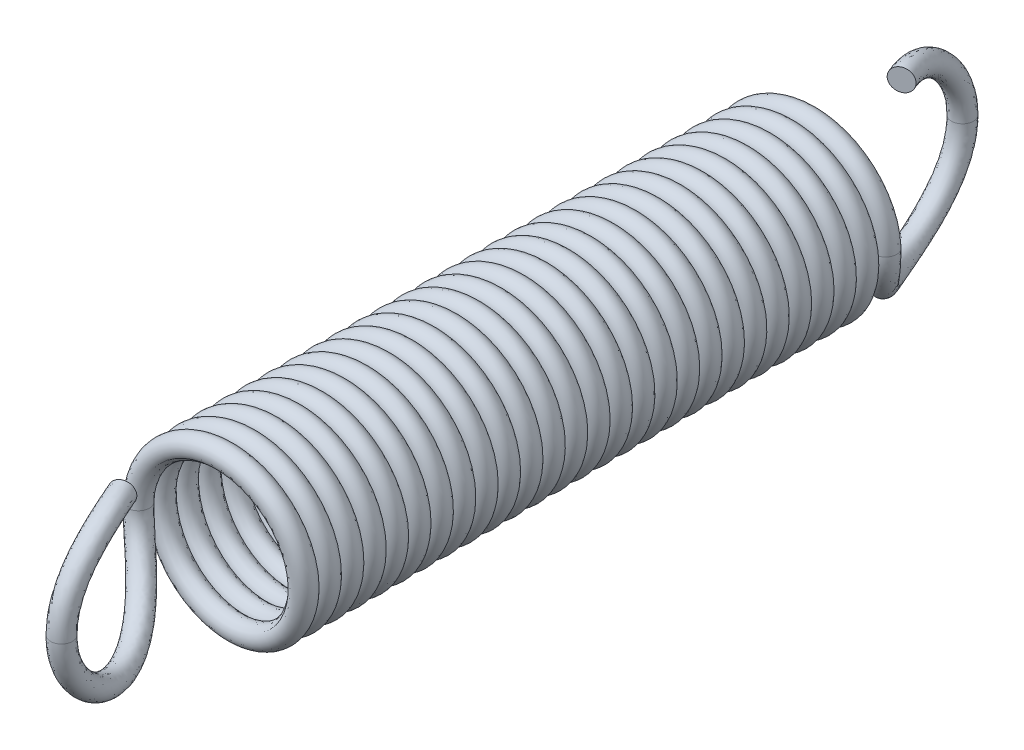
SolidWorks part; units mm, degrees
ref_plane "Front Plane" through (0, 0, 0) normal (0, 0, 1) x (1, 0, 0)
ref_plane "Top Plane" through (0, 0, 0) normal (0, 1, 0) x (1, 0, 0)
ref_plane "Right Plane" through (0, 0, 0) normal (1, 0, 0) x (0, 0, -1)
sketch "Sketch1" plane through (0, 0, 0) normal (1, 0, 0) x (0, 0, -1)
  line L0 (-5, 0) -> (5, 0) construction
  line L1 (5, 0) -> (14.53, 0) construction
  line L2 (-5, 1) -> (-5, -1) construction
  point P4 (0, 0)
  point P6 (-4.75, 0)
  point P9 (-5, 0)
  dimension "OD" = 2
  dimension "Wire Diameter" = 0.25
  dimension "Length" = 10
  dimension "Extended Length" = 19.53
sketch "Sketch2" plane through (0, 0, 0) normal (1, 0, 0) x (0, 0, -1)
  line L1 (-5, 0) -> (-5.25, 0) construction
  line L2 (-4.25, -0.75) -> (-4.25, -1) construction
  line L3 (0, 0) -> (0, 1) construction
  line L4 (-5, 0) -> (-4.75, 0) construction
  line L5 (-5, 0) -> (5, 0) construction
  line L6 (4.25, -0.75) -> (4.25, -1) construction
  line L7 (5, 0) -> (5.25, 0) construction
  line L8 (-4.25, -0.75) -> (4.25, -0.75) construction
  line L9 (-4.25, -1) -> (4.25, -1) construction
  line L10 (-3.25, 0) -> (-3.5, 0) construction
  line L11 (3.5, 0) -> (3.25, 0) construction
  line L12 (-5, 1) -> (-4.25, 1) construction
  circle A0 centre (-4.25, 0) radius 0.75 construction
  circle A2 centre (-4.25, 0) radius 1 construction
  circle A3 centre (4.25, 0) radius 1 construction
  circle A4 centre (4.25, 0) radius 0.75 construction
  point P7 (-2.25, 0)
  point P8 (-4.25, -0.875)
  point P10 (-5.125, 0)
  point P28 (5.125, 0)
  point P33 (-3.375, 0)
  point P34 (3.375, 0)
  point P35 (2.25, 0)
  dimension "OD" = 2
  dimension "D1" = 6.75
  dimension "D2" = 1
  dimension "D3" = 1
ref_plane "Plane1" through (0, 0, 3.375) normal (0, 0, 1) x (1, 0, 0)
sketch "Sketch3" plane through (0, 0, 3.375) normal (0, 0, 1) x (1, 0, 0)
  circle A0 centre (0, 0) radius 0.875
curve "Helix/Spiral1" pitch 0.2547 height 6.75 turns 26.5 parameters "Height"=6.75, "Pitch"=0.2547
sketch "Sketch4" plane through (0, 0, 0) normal (0, 1, 0) x (1, 0, 0)
  circle A0 centre (-0.875, -3.375) radius 0.125
  spline S0 degree 3 poles (-0.875, -3.375) (-0.875, -3.3697) (-0.8294, -3.3591) (-0.6348, -3.3432) (-0.3436, -3.3272) (0, -3.3113) (0.3436, -3.2954) (0.6348, -3.2795) (0.8294, -3.2636) (0.8978, -3.2476) (0.8294, -3.2317) (0.6348, -3.2158) (0.3436, -3.1999) (0, -3.184) (-0.3436, -3.168) (-0.6348, -3.1521) (-0.8294, -3.1362) (-0.8978, -3.1203) (-0.8294, -3.1044) (-0.6348, -3.0884) (-0.3436, -3.0725) (0, -3.0566) (0.3436, -3.0407) (0.6348, -3.0248) (0.8294, -3.0088) (0.8978, -2.9929) (0.8294, -2.977) (0.6348, -2.9611) (0.3436, -2.9452) (0, -2.9292) (-0.3436, -2.9133) (-0.6348, -2.8974) (-0.8294, -2.8815) (-0.8978, -2.8656) (-0.8294, -2.8496) (-0.6348, -2.8337) (-0.3436, -2.8178) (0, -2.8019) (0.3436, -2.786) (0.6348, -2.77) (0.8294, -2.7541) (0.8978, -2.7382) (0.8294, -2.7223) (0.6348, -2.7064) (0.3436, -2.6904) (0, -2.6745) (-0.3436, -2.6586) (-0.6348, -2.6427) (-0.8294, -2.6268) (-0.8978, -2.6108) (-0.8294, -2.5949) (-0.6348, -2.579) (-0.3436, -2.5631) (0, -2.5472) (0.3436, -2.5312) (0.6348, -2.5153) (0.8294, -2.4994) (0.8978, -2.4835) (0.8294, -2.4676) (0.6348, -2.4517) (0.3436, -2.4357) (0, -2.4198) (-0.3436, -2.4039) (-0.6348, -2.388) (-0.8294, -2.3721) (-0.8978, -2.3561) (-0.8294, -2.3402) (-0.6348, -2.3243) (-0.3436, -2.3084) (0, -2.2925) (0.3436, -2.2765) (0.6348, -2.2606) (0.8294, -2.2447) (0.8978, -2.2288) (0.8294, -2.2129) (0.6348, -2.1969) (0.3436, -2.181) (0, -2.1651) (-0.3436, -2.1492) (-0.6348, -2.1333) (-0.8294, -2.1173) (-0.8978, -2.1014) (-0.8294, -2.0855) (-0.6348, -2.0696) (-0.3436, -2.0537) (0, -2.0377) (0.3436, -2.0218) (0.6348, -2.0059) (0.8294, -1.99) (0.8978, -1.9741) (0.8294, -1.9581) (0.6348, -1.9422) (0.3436, -1.9263) (0, -1.9104) (-0.3436, -1.8945) (-0.6348, -1.8785) (-0.8294, -1.8626) (-0.8978, -1.8467) (-0.8294, -1.8308) (-0.6348, -1.8149) (-0.3436, -1.7989) (0, -1.783) (0.3436, -1.7671) (0.6348, -1.7512) (0.8294, -1.7353) (0.8978, -1.7193) (0.8294, -1.7034) (0.6348, -1.6875) (0.3436, -1.6716) (0, -1.6557) (-0.3436, -1.6397) (-0.6348, -1.6238) (-0.8294, -1.6079) (-0.8978, -1.592) (-0.8294, -1.5761) (-0.6348, -1.5601) (-0.3436, -1.5442) (0, -1.5283) (0.3436, -1.5124) (0.6348, -1.4965) (0.8294, -1.4805) (0.8978, -1.4646) (0.8294, -1.4487) (0.6348, -1.4328) (0.3436, -1.4169) (0, -1.4009) (-0.3436, -1.385) (-0.6348, -1.3691) (-0.8294, -1.3532) (-0.8978, -1.3373) (-0.8294, -1.3213) (-0.6348, -1.3054) (-0.3436, -1.2895) (0, -1.2736) (0.3436, -1.2577) (0.6348, -1.2417) (0.8294, -1.2258) (0.8978, -1.2099) (0.8294, -1.194) (0.6348, -1.1781) (0.3436, -1.1621) (0, -1.1462) (-0.3436, -1.1303) (-0.6348, -1.1144) (-0.8294, -1.0985) (-0.8978, -1.0825) (-0.8294, -1.0666) (-0.6348, -1.0507) (-0.3436, -1.0348) (0, -1.0189) (0.3436, -1.0029) (0.6348, -0.987) (0.8294, -0.9711) (0.8978, -0.9552) (0.8294, -0.9393) (0.6348, -0.9233) (0.3436, -0.9074) (0, -0.8915) (-0.3436, -0.8756) (-0.6348, -0.8597) (-0.8294, -0.8438) (-0.8978, -0.8278) (-0.8294, -0.8119) (-0.6348, -0.796) (-0.3436, -0.7801) (0, -0.7642) (0.3436, -0.7482) (0.6348, -0.7323) (0.8294, -0.7164) (0.8978, -0.7005) (0.8294, -0.6846) (0.6348, -0.6686) (0.3436, -0.6527) (0, -0.6368) (-0.3436, -0.6209) (-0.6348, -0.605) (-0.8294, -0.589) (-0.8978, -0.5731) (-0.8294, -0.5572) (-0.6348, -0.5413) (-0.3436, -0.5254) (0, -0.5094) (0.3436, -0.4935) (0.6348, -0.4776) (0.8294, -0.4617) (0.8978, -0.4458) (0.8294, -0.4298) (0.6348, -0.4139) (0.3436, -0.398) (0, -0.3821) (-0.3436, -0.3662) (-0.6348, -0.3502) (-0.8294, -0.3343) (-0.8978, -0.3184) (-0.8294, -0.3025) (-0.6348, -0.2866) (-0.3436, -0.2706) (0, -0.2547) (0.3436, -0.2388) (0.6348, -0.2229) (0.8294, -0.207) (0.8978, -0.191) (0.8294, -0.1751) (0.6348, -0.1592) (0.3436, -0.1433) (0, -0.1274) (-0.3436, -0.1114) (-0.6348, -0.0955) (-0.8294, -0.0796) (-0.8978, -0.0637) (-0.8294, -0.0478) (-0.6348, -0.0318) (-0.3436, -0.0159) (0, 0) (0.3436, 0.0159) (0.6348, 0.0318) (0.8294, 0.0478) (0.8978, 0.0637) (0.8294, 0.0796) (0.6348, 0.0955) (0.3436, 0.1114) (0, 0.1274) (-0.3436, 0.1433) (-0.6348, 0.1592) (-0.8294, 0.1751) (-0.8978, 0.191) (-0.8294, 0.207) (-0.6348, 0.2229) (-0.3436, 0.2388) (0, 0.2547) (0.3436, 0.2706) (0.6348, 0.2866) (0.8294, 0.3025) (0.8978, 0.3184) (0.8294, 0.3343) (0.6348, 0.3502) (0.3436, 0.3662) (0, 0.3821) (-0.3436, 0.398) (-0.6348, 0.4139) (-0.8294, 0.4298) (-0.8978, 0.4458) (-0.8294, 0.4617) (-0.6348, 0.4776) (-0.3436, 0.4935) (0, 0.5094) (0.3436, 0.5254) (0.6348, 0.5413) (0.8294, 0.5572) (0.8978, 0.5731) (0.8294, 0.589) (0.6348, 0.605) (0.3436, 0.6209) (0, 0.6368) (-0.3436, 0.6527) (-0.6348, 0.6686) (-0.8294, 0.6846) (-0.8978, 0.7005) (-0.8294, 0.7164) (-0.6348, 0.7323) (-0.3436, 0.7482) (0, 0.7642) (0.3436, 0.7801) (0.6348, 0.796) (0.8294, 0.8119) (0.8978, 0.8278) (0.8294, 0.8437) (0.6348, 0.8597) (0.3436, 0.8756) (0, 0.8915) (-0.3436, 0.9074) (-0.6348, 0.9233) (-0.8294, 0.9393) (-0.8978, 0.9552) (-0.8294, 0.9711) (-0.6348, 0.987) (-0.3436, 1.0029) (0, 1.0189) (0.3436, 1.0348) (0.6348, 1.0507) (0.8294, 1.0666) (0.8978, 1.0825) (0.8294, 1.0985) (0.6348, 1.1144) (0.3436, 1.1303) (0, 1.1462) (-0.3436, 1.1621) (-0.6348, 1.1781) (-0.8294, 1.194) (-0.8978, 1.2099) (-0.8294, 1.2258) (-0.6348, 1.2417) (-0.3436, 1.2577) (0, 1.2736) (0.3436, 1.2895) (0.6348, 1.3054) (0.8294, 1.3213) (0.8978, 1.3373) (0.8294, 1.3532) (0.6348, 1.3691) (0.3436, 1.385) (0, 1.4009) (-0.3436, 1.4169) (-0.6348, 1.4328) (-0.8294, 1.4487) (-0.8978, 1.4646) (-0.8294, 1.4805) (-0.6348, 1.4965) (-0.3436, 1.5124) (0, 1.5283) (0.3436, 1.5442) (0.6348, 1.5601) (0.8294, 1.5761) (0.8978, 1.592) (0.8294, 1.6079) (0.6348, 1.6238) (0.3436, 1.6397) (0, 1.6557) (-0.3436, 1.6716) (-0.6348, 1.6875) (-0.8294, 1.7034) (-0.8978, 1.7193) (-0.8294, 1.7353) (-0.6348, 1.7512) (-0.3436, 1.7671) (0, 1.783) (0.3436, 1.7989) (0.6348, 1.8149) (0.8294, 1.8308) (0.8978, 1.8467) (0.8294, 1.8626) (0.6348, 1.8785) (0.3436, 1.8945) (0, 1.9104) (-0.3436, 1.9263) (-0.6348, 1.9422) (-0.8294, 1.9581) (-0.8978, 1.9741) (-0.8294, 1.99) (-0.6348, 2.0059) (-0.3436, 2.0218) (0, 2.0377) (0.3436, 2.0537) (0.6348, 2.0696) (0.8294, 2.0855) (0.8978, 2.1014) (0.8294, 2.1173) (0.6348, 2.1333) (0.3436, 2.1492) (0, 2.1651) (-0.3436, 2.181) (-0.6348, 2.1969) (-0.8294, 2.2129) (-0.8978, 2.2288) (-0.8294, 2.2447) (-0.6348, 2.2606) (-0.3436, 2.2765) (0, 2.2925) (0.3436, 2.3084) (0.6348, 2.3243) (0.8294, 2.3402) (0.8978, 2.3561) (0.8294, 2.3721) (0.6348, 2.388) (0.3436, 2.4039) (0, 2.4198) (-0.3436, 2.4357) (-0.6348, 2.4517) (-0.8294, 2.4676) (-0.8978, 2.4835) (-0.8294, 2.4994) (-0.6348, 2.5153) (-0.3436, 2.5313) (0, 2.5472) (0.3436, 2.5631) (0.6348, 2.579) (0.8294, 2.5949) (0.8978, 2.6108) (0.8294, 2.6268) (0.6348, 2.6427) (0.3436, 2.6586) (0, 2.6745) (-0.3436, 2.6904) (-0.6348, 2.7064) (-0.8294, 2.7223) (-0.8978, 2.7382) (-0.8294, 2.7541) (-0.6348, 2.77) (-0.3436, 2.786) (0, 2.8019) (0.3436, 2.8178) (0.6348, 2.8337) (0.8294, 2.8496) (0.8978, 2.8656) (0.8294, 2.8815) (0.6348, 2.8974) (0.3436, 2.9133) (0, 2.9292) (-0.3436, 2.9452) (-0.6348, 2.9611) (-0.8294, 2.977) (-0.8978, 2.9929) (-0.8294, 3.0088) (-0.6348, 3.0248) (-0.3436, 3.0407) (0, 3.0566) (0.3436, 3.0725) (0.6348, 3.0884) (0.8294, 3.1044) (0.8978, 3.1203) (0.8294, 3.1362) (0.6348, 3.1521) (0.3436, 3.168) (0, 3.184) (-0.3436, 3.1999) (-0.6348, 3.2158) (-0.8294, 3.2317) (-0.8978, 3.2476) (-0.8294, 3.2636) (-0.6348, 3.2795) (-0.3436, 3.2954) (0, 3.3113) (0.3436, 3.3272) (0.6348, 3.3432) (0.8294, 3.3591) (0.875, 3.3697) (0.875, 3.375) knots 0 0 0 0 0.002358 0.004717 0.007075 0.009434 0.011792 0.014151 0.016509 0.018868 0.021226 0.023585 0.025943 0.028302 0.03066 0.033019 0.035377 0.037736 0.040094 0.042453 0.044811 0.04717 0.049528 0.051887 0.054245 0.056604 0.058962 0.061321 0.063679 0.066038 0.068396 0.070755 0.073113 0.075472 0.07783 0.080189 0.082547 0.084906 0.087264 0.089623 0.091981 0.09434 0.096698 0.099057 0.101415 0.103774 0.106132 0.108491 0.110849 0.113208 0.115566 0.117925 0.120283 0.122642 0.125 0.127358 0.129717 0.132075 0.134434 0.136792 0.139151 0.141509 0.143868 0.146226 0.148585 0.150943 0.153302 0.15566 0.158019 0.160377 0.162736 0.165094 0.167453 0.169811 0.17217 0.174528 0.176887 0.179245 0.181604 0.183962 0.186321 0.188679 0.191038 0.193396 0.195755 0.198113 0.200472 0.20283 0.205189 0.207547 0.209906 0.212264 0.214623 0.216981 0.21934 0.221698 0.224057 0.226415 0.228774 0.231132 0.233491 0.235849 0.238208 0.240566 0.242925 0.245283 0.247642 0.25 0.252358 0.254717 0.257075 0.259434 0.261792 0.264151 0.266509 0.268868 0.271226 0.273585 0.275943 0.278302 0.28066 0.283019 0.285377 0.287736 0.290094 0.292453 0.294811 0.29717 0.299528 0.301887 0.304245 0.306604 0.308962 0.311321 0.313679 0.316038 0.318396 0.320755 0.323113 0.325472 0.32783 0.330189 0.332547 0.334906 0.337264 0.339623 0.341981 0.34434 0.346698 0.349057 0.351415 0.353774 0.356132 0.358491 0.360849 0.363208 0.365566 0.367925 0.370283 0.372642 0.375 0.377358 0.379717 0.382075 0.384434 0.386792 0.389151 0.391509 0.393868 0.396226 0.398585 0.400943 0.403302 0.40566 0.408019 0.410377 0.412736 0.415094 0.417453 0.419811 0.42217 0.424528 0.426887 0.429245 0.431604 0.433962 0.436321 0.438679 0.441038 0.443396 0.445755 0.448113 0.450472 0.45283 0.455189 0.457547 0.459906 0.462264 0.464623 0.466981 0.46934 0.471698 0.474057 0.476415 0.478774 0.481132 0.483491 0.485849 0.488208 0.490566 0.492925 0.495283 0.497642 0.5 0.502358 0.504717 0.507075 0.509434 0.511792 0.514151 0.516509 0.518868 0.521226 0.523585 0.525943 0.528302 0.53066 0.533019 0.535377 0.537736 0.540094 0.542453 0.544811 0.54717 0.549528 0.551887 0.554245 0.556604 0.558962 0.561321 0.563679 0.566038 0.568396 0.570755 0.573113 0.575472 0.57783 0.580189 0.582547 0.584906 0.587264 0.589623 0.591981 0.59434 0.596698 0.599057 0.601415 0.603774 0.606132 0.608491 0.610849 0.613208 0.615566 0.617925 0.620283 0.622642 0.625 0.627358 0.629717 0.632075 0.634434 0.636792 0.639151 0.641509 0.643868 0.646226 0.648585 0.650943 0.653302 0.65566 0.658019 0.660377 0.662736 0.665094 0.667453 0.669811 0.67217 0.674528 0.676887 0.679245 0.681604 0.683962 0.686321 0.688679 0.691038 0.693396 0.695755 0.698113 0.700472 0.70283 0.705189 0.707547 0.709906 0.712264 0.714623 0.716981 0.71934 0.721698 0.724057 0.726415 0.728774 0.731132 0.733491 0.735849 0.738208 0.740566 0.742925 0.745283 0.747642 0.75 0.752358 0.754717 0.757075 0.759434 0.761792 0.764151 0.766509 0.768868 0.771226 0.773585 0.775943 0.778302 0.78066 0.783019 0.785377 0.787736 0.790094 0.792453 0.794811 0.79717 0.799528 0.801887 0.804245 0.806604 0.808962 0.811321 0.813679 0.816038 0.818396 0.820755 0.823113 0.825472 0.82783 0.830189 0.832547 0.834906 0.837264 0.839623 0.841981 0.84434 0.846698 0.849057 0.851415 0.853774 0.856132 0.858491 0.860849 0.863208 0.865566 0.867925 0.870283 0.872642 0.875 0.877358 0.879717 0.882075 0.884434 0.886792 0.889151 0.891509 0.893868 0.896226 0.898585 0.900943 0.903302 0.90566 0.908019 0.910377 0.912736 0.915094 0.917453 0.919811 0.92217 0.924528 0.926887 0.929245 0.931604 0.933962 0.936321 0.938679 0.941038 0.943396 0.945755 0.948113 0.950472 0.95283 0.955189 0.957547 0.959906 0.962264 0.964623 0.966981 0.96934 0.971698 0.974057 0.976415 0.978774 0.981132 0.983491 0.985849 0.988208 0.990566 0.992925 0.995283 0.997642 1 1 1 1 construction
  dimension "D1" = 0.25
sweep "Spring Body Sweep" add profiles "Sketch4" path "Helix/Spiral1"
sketch "Sketch5" plane through (0, 0, 0) normal (1, 0, 0) x (0, 0, -1)
  line L0 (-3.5, 0) -> (-3.25, 0) construction
  line L1 (-3.5, 0) -> (-3.25, 0) construction
  line L2 (-5, 0) -> (5, 0) construction
  arc A1 (-3.375, 0) -> (-4.25, 0.875) centre (-4.25, 0) cw
sketch "Sketch6" plane through (0, 0, 0) normal (0, 1, 0) x (1, 0, 0)
  line L2 (-0.875, -3.25) -> (-0.875, -3.5) construction
  line L3 (-0.875, -3.375) -> (0.875, -3.375) construction
  line L4 (0, -5) -> (0, -5.25) construction
  line L5 (0, -5.125) -> (0, -3.375) construction
  arc A2 (-0.875, -3.375) -> (0, -5.125) centre (-2.1875, -5.125) cw
sketch "Sketch7" plane through (0, 0, 0) normal (0, -1, 0) x (1, 0, 0)
  circle A1 centre (-0.875, 3.375) radius 0.125
  circle A3 centre (-0.875, 3.375) radius 0.125
  dimension "D1" = 0
ref_axis "Axis1" through (0, 2.5403, 0) along (0, -1, 0)
curve "Curve1"
sweep "Spring Hook Sweep" add profiles "Sketch7" path "Curve1"
pattern_circular "Spring Hook CirPattern" count 2 over 360 about axis through (0, 2.5403, 0) along (0, -1, 0) of "Spring Hook Sweep"
equation "\"D1@Sketch4\" = \"Wire Diameter@Sketch1\""
equation "\"Height@Helix/Spiral1\"=\"D1@Sketch2\""
equation "\"D2@Sketch2\" = 4 * \"Wire Diameter@Sketch1\""
equation "\"D3@Sketch2\"=\"D2@Sketch2\""
